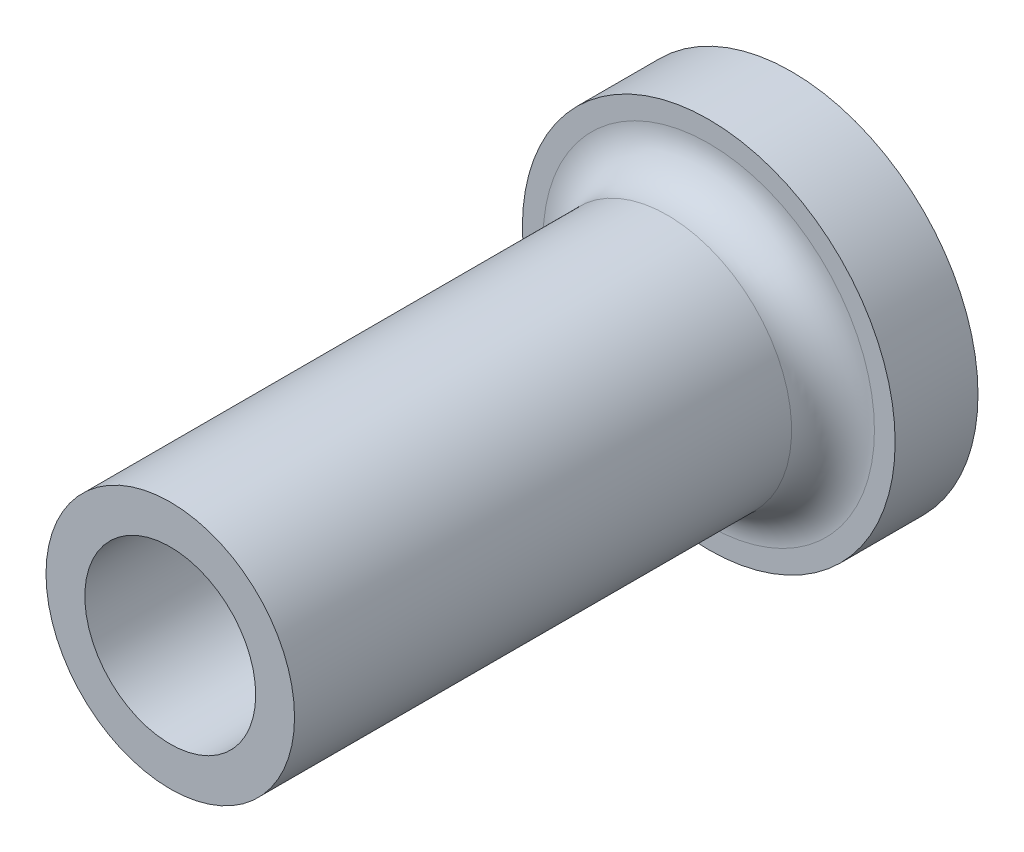
SolidWorks part; units mm, degrees
ref_plane "Front Plane" through (0, 0, 0) normal (0, 0, 1) x (1, 0, 0)
ref_plane "Top Plane" through (0, 0, 0) normal (0, 1, 0) x (1, 0, 0)
ref_plane "Right Plane" through (0, 0, 0) normal (1, 0, 0) x (0, 0, -1)
sketch "Sketch1" plane through (0, 0, 0) normal (0, 0, 1) x (1, 0, 0)
  circle A0 centre (0, 0) radius 4.125
  circle A1 centre (0, 0) radius 6
  dimension "D1" = 8.25
  dimension "D2" = 12
extrude "Boss-Extrude1" add sketch "Sketch1" along normal blind 30
sketch "Sketch2" plane through (0, 0, 0) normal (0, 0, -1) x (-1, 0, 0)
  circle A0 centre (0, 0) radius 4.125
  circle A1 centre (0, 0) radius 9
  circle A2 centre (0, 0) radius 4.125 construction
  dimension "D1" = 18
extrude "Boss-Extrude2" add sketch "Sketch2" against normal blind 4
fillet "Fillet1" radius 2 1 edges at (-6, 0, 4)
